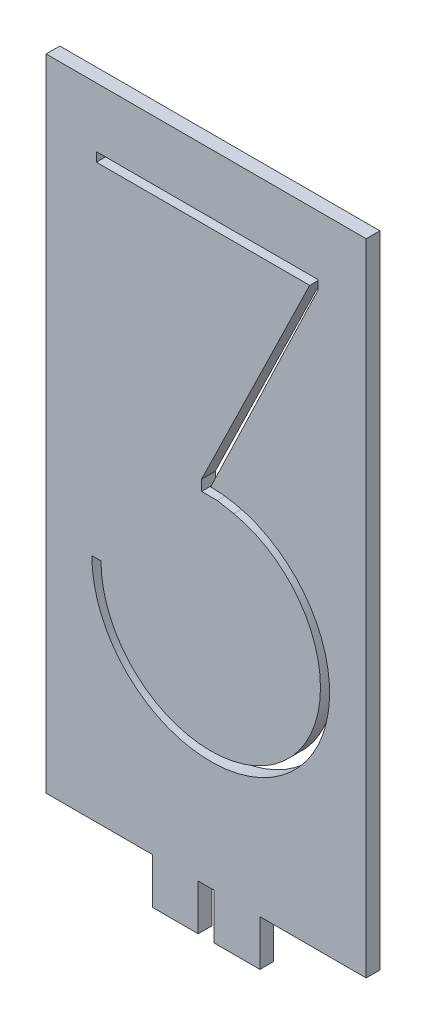
SolidWorks part; units mm, degrees
material "Glas"
ref_plane "Ebene vorne" through (0, 0, 0) normal (0, 0, 1) x (1, 0, 0)
ref_plane "Ebene oben" through (0, 0, 0) normal (0, 1, 0) x (1, 0, 0)
ref_plane "Ebene rechts" through (0, 0, 0) normal (1, 0, 0) x (0, 0, -1)
sketch "Skizze1" plane through (0, 0, 0) normal (0, 0, 1) x (1, 0, 0)
  line L1 (0, 0) -> (35, 0)
  line L2 (0, 0) -> (0, 75)
  line L3 (0, 75) -> (35, 75)
  line L4 (35, 0) -> (35, 75)
  dimension "D1" = 35
  dimension "D2" = 75
extrude "Aufsatz-Linear austragen1" add sketch "Skizze1" along normal blind 1.5
sketch "Skizze2" plane through (0, 0, 1.5) normal (0, 0, 1) x (1, 0, 0)
  line L0 (0, 0) -> (35, 0) construction
  line L1 (0, 0) -> (11.63, 0)
  line L2 (0, 0) -> (0, 5)
  line L3 (0, 5) -> (11.63, 5)
  line L4 (11.63, 0) -> (11.63, 5)
  line L5 (23.38, 5) -> (35, 5)
  line L6 (23.38, 5) -> (23.38, 0)
  line L7 (23.38, 0) -> (35, 0)
  line L8 (35, 5) -> (35, 0)
  line L9 (16.63, 0) -> (18.38, 0)
  line L10 (16.63, 0) -> (16.63, 5)
  line L11 (16.63, 5) -> (18.38, 5)
  line L12 (18.38, 0) -> (18.38, 5)
  dimension "D1" = 5
  dimension "D2" = 5
  dimension "D3" = 5
  dimension "D4" = 11.63
  dimension "D5" = 1.75
  dimension "D6" = 5
extrude "Schnitt-Linear austragen1" cut sketch "Skizze2" against normal blind 1.5
sketch "Skizze9" plane through (0, 0, 1.5) normal (0, 0, 1) x (1, 0, 0)
  line L1 (18, 43) -> (29.7349, 67.5)
  line L3 (5, 30) -> (6, 30)
  line L7 (35, 5) -> (35, 75) construction
  line L8 (35, 5) -> (23.38, 5) construction
  line L16 (17, 43.2307) -> (28.8265, 67.5)
  line L17 (28.8265, 67.5) -> (5.5, 67.5)
  line L22 (29.7349, 67.5) -> (29.7349, 68.5)
  line L23 (29.7349, 68.5) -> (5.5, 68.5)
  line L24 (5.5, 68.5) -> (5.5, 67.5)
  line L25 (20.528, 41.7307) -> (19.5472, 41.9154)
  line L26 (19.5472, 41.9154) -> (18.7316, 42.069)
  line L30 (18.7316, 42.069) -> (17, 42.069)
  line L31 (17, 42.069) -> (17, 43.2307)
  arc A1 (20.528, 41.7307) -> (6, 30) centre (18, 30) cw
  arc A2 (5, 30) -> (18, 43) centre (18, 30) ccw
  dimension "D1" = 1
  dimension "D2" = 13
  dimension "D4" = 17
  dimension "D5" = 1
  dimension "D9" = 1.0263
  dimension "D3" = 25
extrude "Schnitt-Linear austragen4" cut sketch "Skizze9" against normal blind 20
